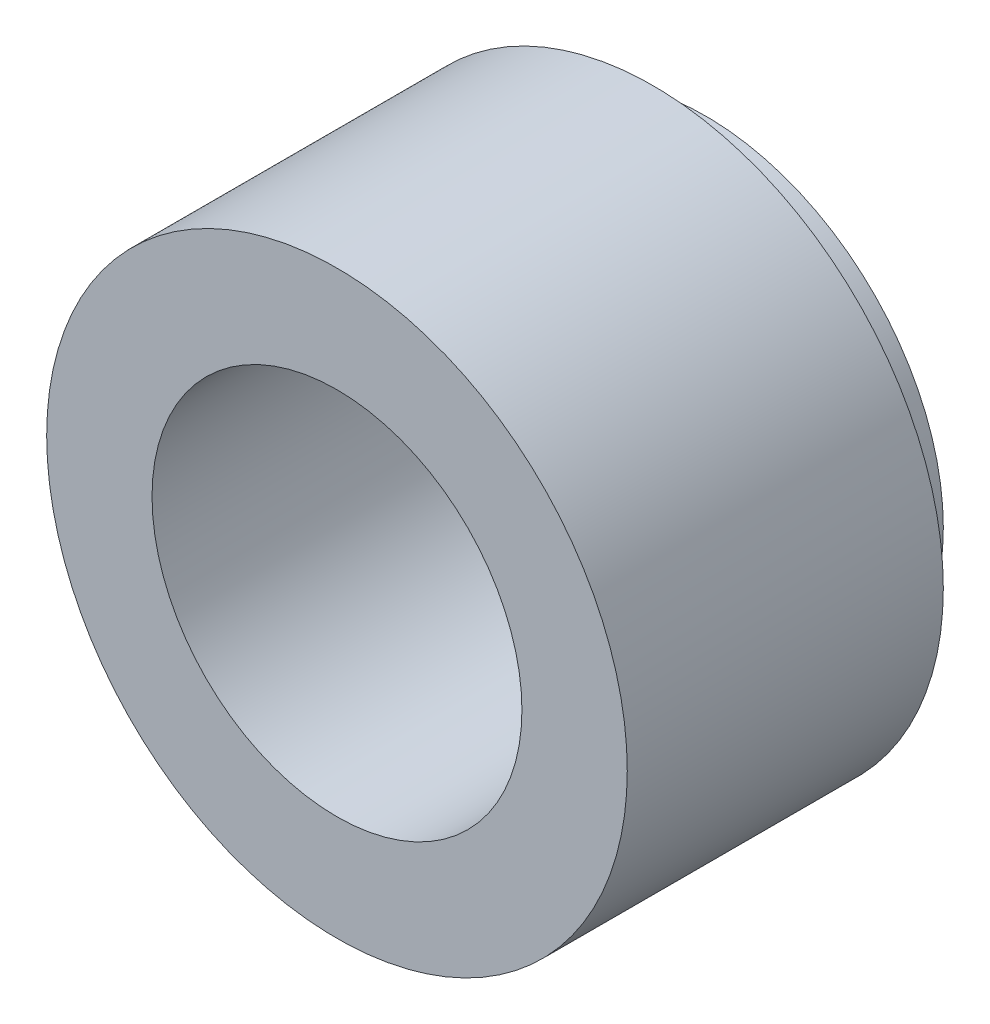
SolidWorks part; units mm, degrees
ref_plane "Front Plane" through (0, 0, 0) normal (0, 0, 1) x (1, 0, 0)
ref_plane "Top Plane" through (0, 0, 0) normal (0, 1, 0) x (1, 0, 0)
ref_plane "Right Plane" through (0, 0, 0) normal (1, 0, 0) x (0, 0, -1)
sketch "Sketch1" plane through (0, 0, 0) normal (1, 0, 0) x (0, 0, -1)
  line L0 (-13.1455, 10.117) -> (-13.1455, 17.3509)
  line L1 (-13.1455, 17.3509) -> (8.5563, 17.3509)
  line L2 (8.5563, 17.3509) -> (8.5563, 13.7339)
  line L3 (8.5563, 13.7339) -> (12.1733, 13.7339)
  line L4 (12.1733, 13.7339) -> (12.1733, 10.117)
  line L5 (12.1733, 10.117) -> (-13.1455, 10.117)
  line L6 (-33.7232, -2.583) -> (48.693, -2.583) construction
  dimension "D1" = 3.617
  dimension "D2" = 3.617
  dimension "D3" = 25.3187
  dimension "D4" = 21.7018
  dimension "D5" = 12.7
revolve "Revolve1" add sketch "Sketch1" angle 360 about L6
